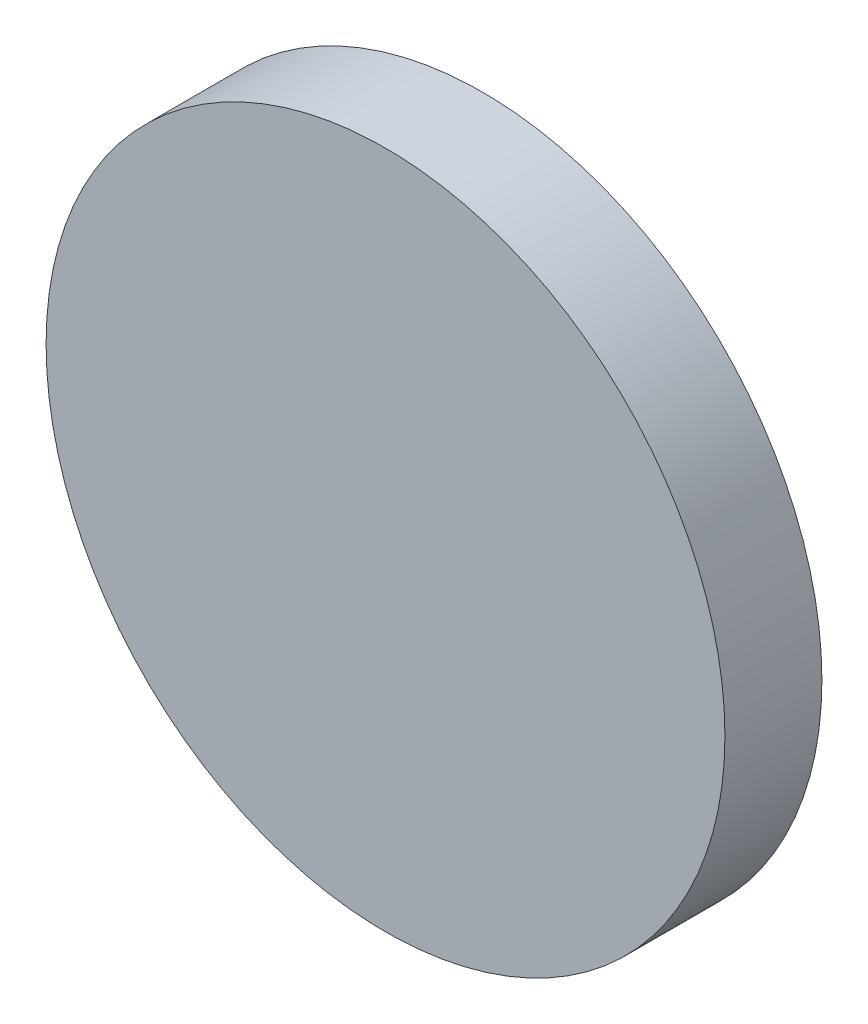
SolidWorks part; units mm, degrees
ref_plane "Front Plane" through (0, 0, 0) normal (0, 0, 1) x (1, 0, 0)
ref_plane "Top Plane" through (0, 0, 0) normal (0, 1, 0) x (1, 0, 0)
ref_plane "Right Plane" through (0, 0, 0) normal (1, 0, 0) x (0, 0, -1)
sketch "Sketch1" plane through (0, 0, 0) normal (0, 0, 1) x (1, 0, 0)
  circle A0 centre (0, 0) radius 3.5
  dimension "D1" = 7
extrude "Boss-Extrude1" add sketch "Sketch1" along normal blind 1
